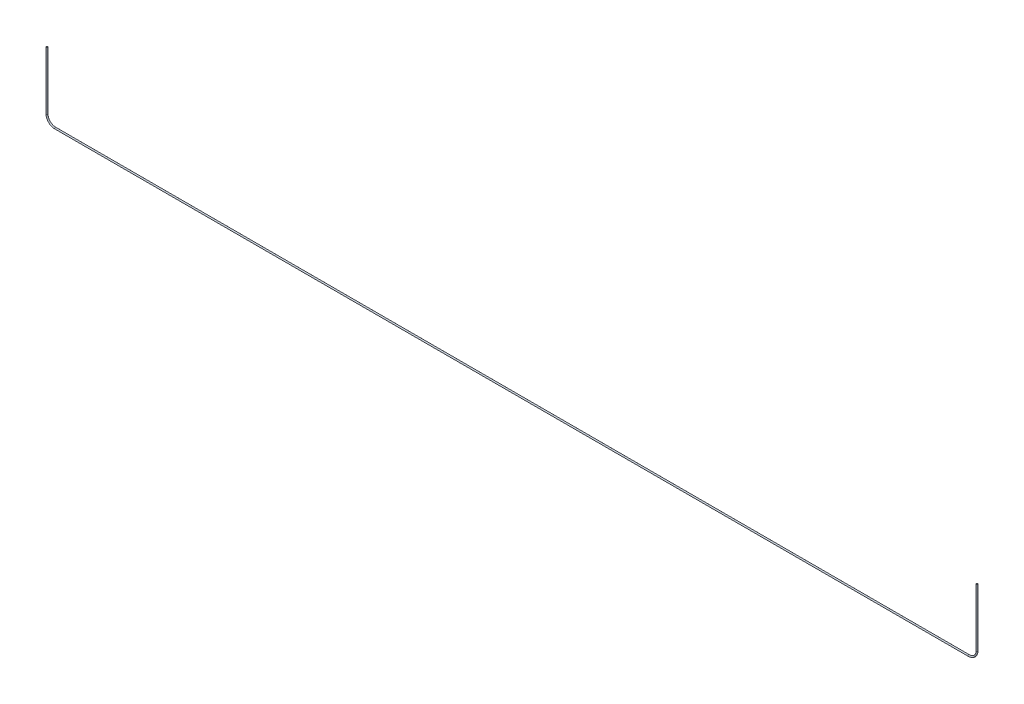
SolidWorks part; units mm, degrees
ref_plane "Front Plane" through (0, 0, 0) normal (0, 0, 1) x (1, 0, 0)
ref_plane "Top Plane" through (0, 0, 0) normal (0, 1, 0) x (1, 0, 0)
ref_plane "Right Plane" through (0, 0, 0) normal (1, 0, 0) x (0, 0, -1)
sketch "Sketch1" plane through (0, 0, 0) normal (0, 0, 1) x (1, 0, 0)
  line L0 (4145, 0) -> (-4145, 0)
  line L1 (-4220, 75) -> (-4220, 600)
  line L2 (0, 679.5766) -> (0, -698.3937) construction
  line L3 (4220, 75) -> (4220, 600)
  arc A0 (-4145, 0) -> (-4220, 75) centre (-4145, 75) cw
  arc A1 (4145, 0) -> (4220, 75) centre (4145, 75) ccw
  point P6 (-4220, 0)
  point P12 (0, 0)
  dimension "D3" = 75
  dimension "D1" = 4220
  dimension "D2" = 600
sweep "Sweep1" add path "Sketch1" circular profile diameter 12.7 parameters "D3"=12.7
